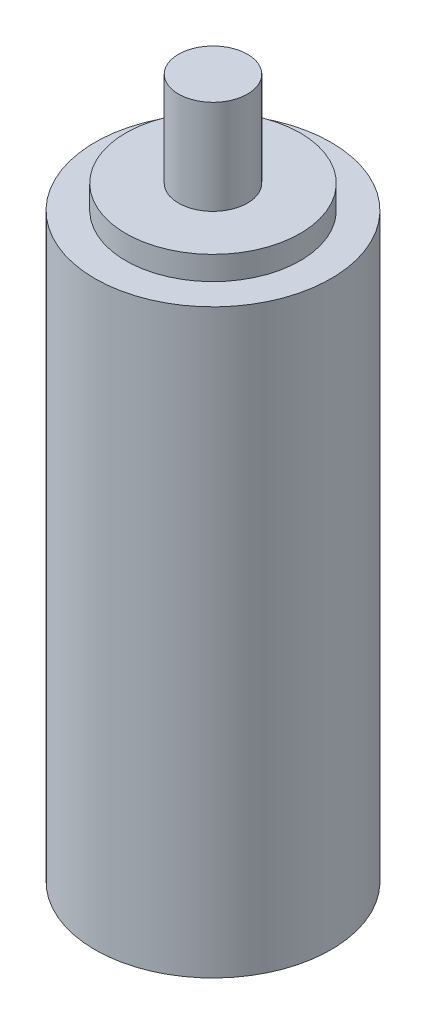
SolidWorks part; units mm, degrees
ref_plane "Front" through (0, 0, 0) normal (0, 0, 1) x (1, 0, 0)
ref_plane "Top" through (0, 0, 0) normal (0, 1, 0) x (1, 0, 0)
ref_plane "Right" through (0, 0, 0) normal (1, 0, 0) x (0, 0, -1)
sketch "Sketch1" plane through (0, 0, 0) normal (0, 1, 0) x (1, 0, 0)
  circle A0 centre (0, 0) radius 32.5
  dimension "D1" = 65
extrude "Boss-Extrude1" add sketch "Sketch1" along normal blind 160
sketch "Sketch2" plane through (0, 160, 0) normal (0, 1, 0) x (1, 0, 0)
  circle A0 centre (0, 0) radius 24
  dimension "D1" = 48
extrude "Boss-Extrude2" add sketch "Sketch2" along normal blind 6.5
sketch "Sketch3" plane through (0, 166.5, 0) normal (0, 1, 0) x (1, 0, 0)
  circle A0 centre (0, 0) radius 9.5
  dimension "D1" = 19
extrude "Boss-Extrude3" add sketch "Sketch3" along normal blind 26
